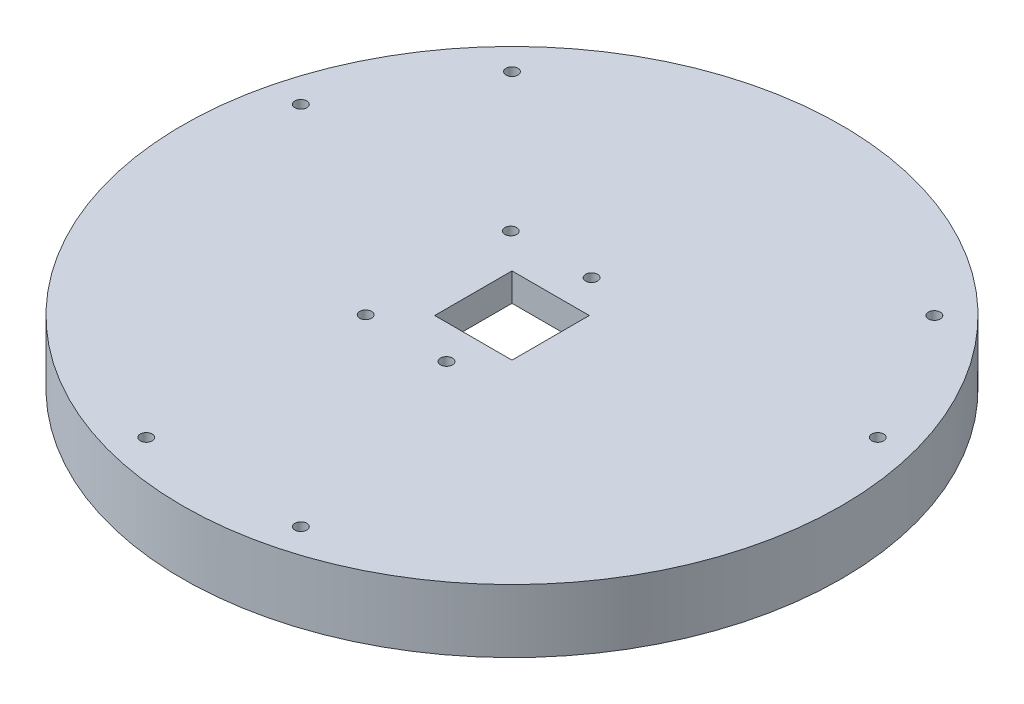
SolidWorks part; units mm, degrees
ref_plane "前视基准面" through (0, 0, 0) normal (0, 0, 1) x (1, 0, 0)
ref_plane "上视基准面" through (0, 0, 0) normal (0, 1, 0) x (1, 0, 0)
ref_plane "右视基准面" through (0, 0, 0) normal (1, 0, 0) x (0, 0, -1)
other "Configuration Table"
sketch "草图1" plane through (0, 0, 0) normal (0, 1, 0) x (1, 0, 0)
  circle A0 centre (0, 0) radius 46
  dimension "D1" = 92
extrude "拉伸-薄壁2" add sketch "草图1" along normal blind 5 thin contours A0 thin type mid plane wall 1.8
sketch "草图2" plane through (0, 5, 0) normal (0, 1, 0) x (1, 0, 0)
  circle A0 centre (0, 0) radius 46.9 construction
  circle A1 centre (0, 0) radius 46.9
extrude "凸台-拉伸1" add sketch "草图2" along normal blind 4
sketch "草图4" plane through (0, 5, 0) normal (0, -1, 0) x (1, 0, 0)
  line L5 (-5.5, 5.5) -> (5.5, 5.5)
  line L6 (-5.5, 5.5) -> (-5.5, -5.5)
  line L11 (-5.5, -5.5) -> (5.5, -5.5)
  line L12 (5.5, 5.5) -> (5.5, -5.5)
  line L13 (-5.5, 5.5) -> (5.5, -5.5) construction
  line L14 (-5.5, -5.5) -> (5.5, 5.5) construction
  line L15 (-12.5, 12.5) -> (10.5, 12.5)
  line L16 (-12.5, 12.5) -> (-12.5, -12.5)
  line L17 (-12.5, -12.5) -> (10.5, -12.5)
  line L18 (10.5, 12.5) -> (10.5, -12.5)
  line L19 (-12.5, 12.5) -> (10.5, -12.5) construction
  line L20 (-12.5, -12.5) -> (10.5, 12.5) construction
  point P0 (0, 0)
  point P6 (-1, 0)
  point P11 (-10.5, 10.3261)
  point P16 (-10.5, -10.3261)
  point P17 (1, 10.3261)
  point P18 (1, -10.3261)
  dimension "D1" = 11
  dimension "D2" = 11
  dimension "D3" = 23
  dimension "D4" = 25
  dimension "D5" = 5
  dimension "D6" = 2
  dimension "D7" = 2
  dimension "D8" = 9.5
  dimension "D9" = 9.5
extrude "切除-拉伸1" cut sketch "草图4" against normal through all contours L12 L5 L6 L11
hole_wizard "孔2" positions "草图14" profile "草图15" legacy
sketch "草图14" plane through (0, 5, 0) normal (0, -1, 0) x (-1, 0, 0)
  point P0 (-1, 10.3261)
  point P3 (10.5, 10.3261)
  point P6 (10.5, -10.3261)
  point P9 (-1, -10.3261)
sketch "草图15" plane through (1, 5, -10.3261) normal (1, 0, 0) x (0, 0, -1)
  line L0 (0, 0) -> (0, 4.4)
  line L1 (0, 4.4) -> (0.85, 4.4)
  line L2 (0.85, 4.4) -> (0.85, 0)
  line L3 (0.85, 0) -> (0, 0)
  line L4 (0, 110) -> (0, -10) construction
  dimension "直径" = 1.7
  dimension "深度" = 4.4
chamfer "倒角1" distance 0.3 angle 45 1 edges at (45.1, 0, 0)
sketch "草图16" plane through (0, 9, 0) normal (0, 1, 0) x (1, 0, 0)
  line L0 (0, 0) -> (0, -41.1766) construction
  line L1 (0, 0) -> (-35.66, 20.5883) construction
  line L2 (0, 0) -> (35.66, 20.5883) construction
  arc A0 (-10.9998, -41.0518) -> (10.9998, -41.0518) centre (0, 0) ccw
  arc A1 (-30.052, 30.052) -> (-41.0518, 10.9998) centre (0, 0) ccw
  arc A2 (41.0518, 10.9998) -> (30.052, 30.052) centre (0, 0) ccw
  point P13 (0, 0)
  dimension "D1" = 42.5
  dimension "D2" = 30
  dimension "D3" = 3
hole_wizard "孔1" positions "草图17" profile "草图18" legacy end condition up to next
sketch "草图17" plane through (0, 9, 0) normal (0, 1, 0) x (1, 0, 0)
  point P0 (-41.0518, 10.9998)
  point P3 (-30.052, 30.052)
  point P6 (30.052, 30.052)
  point P9 (41.0518, 10.9998)
  point P12 (10.9998, -41.0518)
  point P15 (-10.9998, -41.0518)
sketch "草图18" plane through (-41.0518, 9, -10.9998) normal (1, 0, 0) x (0, 0, 1)
  line L0 (0, 0) -> (0, 4)
  line L1 (0, 4) -> (0.85, 4)
  line L2 (0.85, 4) -> (0.85, 0)
  line L3 (0.85, 0) -> (0, 0)
  line L4 (0, 110) -> (0, -10) construction
  dimension "直径" = 1.7
  dimension "深度" = 4
sketch "草图20" plane through (0, 5, 0) normal (0, -1, 0) x (1, 0, 0)
  line L0 (-17.6683, 35.8864) -> (-17.6683, 41.3864)
  line L1 (17.6683, 35.8864) -> (17.6683, 41.3864)
  line L3 (21.4884, 33.7379) -> (21.4884, 39.5379)
  arc A0 (21.4884, 33.7379) -> (-17.6683, 35.8864) centre (0, 0) ccw
  arc A1 (21.4884, 39.5379) -> (-17.6683, 41.3864) centre (0, 0) ccw
  dimension "D1" = 80
  dimension "D2" = 90
  dimension "D3" = 5.5
  dimension "D4" = 5.5
  dimension "D5" = 5.8
extrude "凸台-拉伸2" add sketch "草图20" along normal blind 4 contours L3 A1 L1 A0
